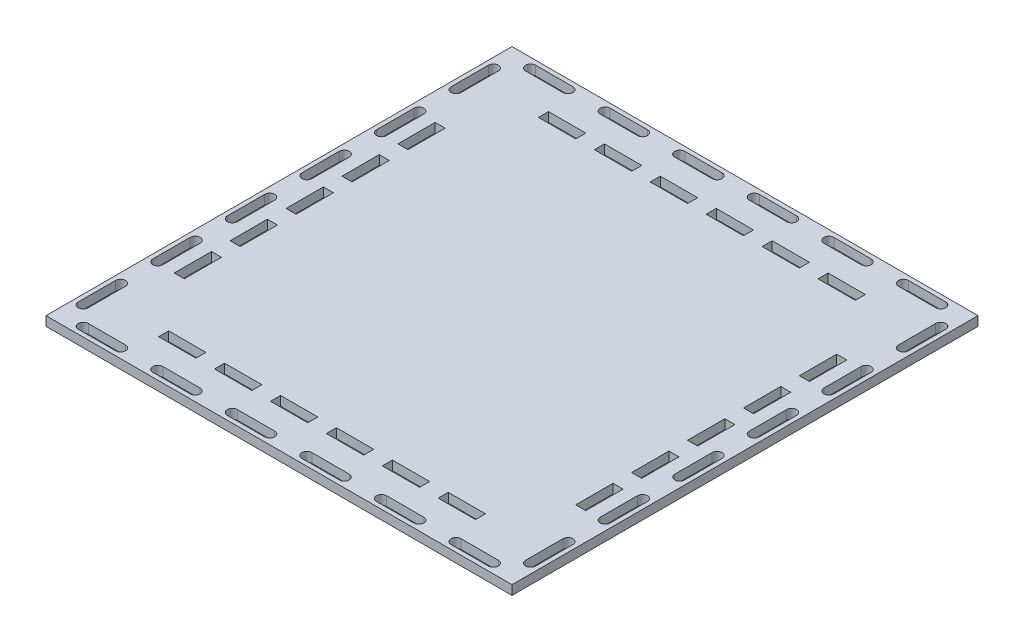
SolidWorks part; units mm, degrees
ref_plane "Front Plane" through (0, 0, 0) normal (0, 0, 1) x (1, 0, 0)
ref_plane "Top Plane" through (0, 0, 0) normal (0, 1, 0) x (1, 0, 0)
ref_plane "Right Plane" through (0, 0, 0) normal (1, 0, 0) x (0, 0, -1)
sketch "Sketch1" plane through (0, 0, 0) normal (0, 1, 0) x (1, 0, 0)
  line L1 (-158.75, -158.75) -> (158.75, -158.75)
  line L2 (-158.75, -158.75) -> (-158.75, 158.75)
  line L3 (-158.75, 158.75) -> (158.75, 158.75)
  line L4 (158.75, -158.75) -> (158.75, 158.75)
  line L5 (-158.75, -158.75) -> (158.75, 158.75) construction
  line L6 (-158.75, 158.75) -> (158.75, -158.75) construction
  point P0 (0, 0)
  dimension "D1" = 317.5
  dimension "D2" = 317.5
extrude "Boss-Extrude1" add sketch "Sketch1" along normal blind 6.35
sketch "Sketch2" plane through (0, 0, 0) normal (0, 1, 0) x (1, 0, 0)
  line L1 (-107.95, 132.8195) -> (-82.55, 132.8195)
  line L2 (-107.95, 132.8195) -> (-107.95, 125.9615)
  line L3 (-107.95, 125.9615) -> (-82.55, 125.9615)
  line L4 (-82.55, 132.8195) -> (-82.55, 125.9615)
  line L10 (-44.45, 132.8195) -> (-44.45, 125.9615)
  line L15 (-69.85, 125.9615) -> (-44.45, 125.9615)
  line L16 (-69.85, 132.8195) -> (-44.45, 132.8195)
  line L17 (-69.85, 132.8195) -> (-69.85, 125.9615)
  line L18 (-6.35, 132.8195) -> (-6.35, 125.9615)
  line L19 (-31.75, 125.9615) -> (-6.35, 125.9615)
  line L20 (-31.75, 132.8195) -> (-6.35, 132.8195)
  line L21 (-31.75, 132.8195) -> (-31.75, 125.9615)
  line L22 (31.75, 132.8195) -> (31.75, 125.9615)
  line L23 (6.35, 125.9615) -> (31.75, 125.9615)
  line L24 (6.35, 132.8195) -> (31.75, 132.8195)
  line L25 (6.35, 132.8195) -> (6.35, 125.9615)
  line L26 (69.85, 132.8195) -> (69.85, 125.9615)
  line L27 (44.45, 125.9615) -> (69.85, 125.9615)
  line L28 (44.45, 132.8195) -> (69.85, 132.8195)
  line L29 (44.45, 132.8195) -> (44.45, 125.9615)
  line L30 (107.95, 132.8195) -> (107.95, 125.9615)
  line L31 (82.55, 125.9615) -> (107.95, 125.9615)
  line L32 (82.55, 132.8195) -> (107.95, 132.8195)
  line L33 (82.55, 132.8195) -> (82.55, 125.9615)
  line L50 (184.15, 132.8195) -> (184.15, 125.9615) [skipped]
  line L51 (158.75, 125.9615) -> (184.15, 125.9615) [skipped]
  line L52 (158.75, 132.8195) -> (184.15, 132.8195) [skipped]
  line L53 (158.75, 132.8195) -> (158.75, 125.9615) [skipped]
  line L54 (222.25, 132.8195) -> (222.25, 125.9615) [skipped]
  line L55 (196.85, 125.9615) -> (222.25, 125.9615) [skipped]
  line L56 (196.85, 132.8195) -> (222.25, 132.8195) [skipped]
  line L57 (196.85, 132.8195) -> (196.85, 125.9615) [skipped]
  line L58 (260.35, 132.8195) -> (260.35, 125.9615) [skipped]
  line L59 (234.95, 125.9615) -> (260.35, 125.9615) [skipped]
  line L60 (234.95, 132.8195) -> (260.35, 132.8195) [skipped]
  line L61 (234.95, 132.8195) -> (234.95, 125.9615) [skipped]
  line L62 (-6.35, 125.9615) -> (6.35, 125.9615) construction
  line L63 (0, 125.9615) -> (0, 158.75) construction
  line L64 (146.05, 132.8195) -> (146.05, 125.9615) [skipped]
  line L65 (120.65, 125.9615) -> (146.05, 125.9615) [skipped]
  line L66 (120.65, 132.8195) -> (146.05, 132.8195) [skipped]
  line L67 (120.65, 132.8195) -> (120.65, 125.9615) [skipped]
  line L68 (158.75, 158.75) -> (-158.75, 158.75) construction
  line L75 (-140.208, 49.7615) -> (-140.208, 24.3615)
  line L76 (-140.208, 87.8615) -> (-133.35, 87.8615)
  line L77 (-140.208, 87.8615) -> (-140.208, 62.4615)
  line L78 (-140.208, 62.4615) -> (-133.35, 62.4615)
  line L79 (-133.35, 87.8615) -> (-133.35, 62.4615)
  line L80 (-140.208, 24.3615) -> (-133.35, 24.3615)
  line L81 (-133.35, 49.7615) -> (-133.35, 24.3615)
  line L82 (-140.208, 49.7615) -> (-133.35, 49.7615)
  line L83 (-140.208, 11.6615) -> (-140.208, -13.7385)
  line L84 (-140.208, -13.7385) -> (-133.35, -13.7385)
  line L85 (-133.35, 11.6615) -> (-133.35, -13.7385)
  line L86 (-140.208, 11.6615) -> (-133.35, 11.6615)
  line L87 (-140.208, -26.4385) -> (-140.208, -51.8385)
  line L88 (-140.208, -51.8385) -> (-133.35, -51.8385)
  line L89 (-133.35, -26.4385) -> (-133.35, -51.8385)
  line L90 (-140.208, -26.4385) -> (-133.35, -26.4385)
  line L91 (-140.208, -64.5385) -> (-140.208, -89.9385)
  line L92 (-140.208, -89.9385) -> (-133.35, -89.9385)
  line L93 (-133.35, -64.5385) -> (-133.35, -89.9385)
  line L94 (-140.208, -64.5385) -> (-133.35, -64.5385)
  line L95 (140.208, -64.5385) -> (133.35, -64.5385)
  line L96 (133.35, -64.5385) -> (133.35, -89.9385)
  line L97 (140.208, -89.9385) -> (133.35, -89.9385)
  line L98 (140.208, -64.5385) -> (140.208, -89.9385)
  line L99 (140.208, -26.4385) -> (133.35, -26.4385)
  line L100 (133.35, -26.4385) -> (133.35, -51.8385)
  line L101 (140.208, -51.8385) -> (133.35, -51.8385)
  line L102 (140.208, -26.4385) -> (140.208, -51.8385)
  line L103 (140.208, 11.6615) -> (133.35, 11.6615)
  line L104 (133.35, 11.6615) -> (133.35, -13.7385)
  line L105 (140.208, -13.7385) -> (133.35, -13.7385)
  line L106 (140.208, 11.6615) -> (140.208, -13.7385)
  line L107 (140.208, 49.7615) -> (133.35, 49.7615)
  line L108 (133.35, 49.7615) -> (133.35, 24.3615)
  line L109 (140.208, 24.3615) -> (133.35, 24.3615)
  line L110 (133.35, 87.8615) -> (133.35, 62.4615)
  line L111 (140.208, 62.4615) -> (133.35, 62.4615)
  line L112 (140.208, 87.8615) -> (140.208, 62.4615)
  line L113 (140.208, 87.8615) -> (133.35, 87.8615)
  line L114 (140.208, 49.7615) -> (140.208, 24.3615)
  line L115 (0, 0) -> (44.45, 0) construction
  line L116 (-139.7, 155.829) -> (-114.3, 155.829)
  line L117 (-6.35, -125.9615) -> (6.35, -125.9615) construction
  line L124 (82.55, -132.8195) -> (82.55, -125.9615)
  line L125 (82.55, -132.8195) -> (107.95, -132.8195)
  line L126 (82.55, -125.9615) -> (107.95, -125.9615)
  line L127 (107.95, -132.8195) -> (107.95, -125.9615)
  line L128 (44.45, -132.8195) -> (44.45, -125.9615)
  line L129 (44.45, -132.8195) -> (69.85, -132.8195)
  line L130 (44.45, -125.9615) -> (69.85, -125.9615)
  line L131 (69.85, -132.8195) -> (69.85, -125.9615)
  line L132 (6.35, -132.8195) -> (6.35, -125.9615)
  line L133 (6.35, -132.8195) -> (31.75, -132.8195)
  line L134 (6.35, -125.9615) -> (31.75, -125.9615)
  line L135 (31.75, -132.8195) -> (31.75, -125.9615)
  line L136 (-31.75, -132.8195) -> (-31.75, -125.9615)
  line L137 (-31.75, -132.8195) -> (-6.35, -132.8195)
  line L138 (-31.75, -125.9615) -> (-6.35, -125.9615)
  line L139 (-6.35, -132.8195) -> (-6.35, -125.9615)
  line L140 (-69.85, -132.8195) -> (-69.85, -125.9615)
  line L141 (-69.85, -132.8195) -> (-44.45, -132.8195)
  line L142 (-69.85, -125.9615) -> (-44.45, -125.9615)
  line L143 (-44.45, -132.8195) -> (-44.45, -125.9615)
  line L149 (-82.55, -132.8195) -> (-82.55, -125.9615)
  line L150 (-107.95, -125.9615) -> (-82.55, -125.9615)
  line L151 (-107.95, -132.8195) -> (-107.95, -125.9615)
  line L152 (-107.95, -132.8195) -> (-82.55, -132.8195)
  line L154 (-88.9, 155.829) -> (-63.5, 155.829)
  line L155 (-158.75, 158.75) -> (-158.75, -158.75) construction
  line L156 (-155.829, 139.7) -> (-155.829, 114.3)
  line L157 (-148.971, 114.3) -> (-148.971, 139.7)
  line L158 (-148.971, 63.5) -> (-148.971, 88.9)
  line L159 (-155.829, 88.9) -> (-155.829, 63.5)
  line L160 (-148.971, 12.7) -> (-148.971, 38.1)
  line L161 (-155.829, 38.1) -> (-155.829, 12.7)
  line L162 (-148.971, -38.1) -> (-148.971, -12.7)
  line L163 (-155.829, -12.7) -> (-155.829, -38.1)
  line L164 (-148.971, -88.9) -> (-148.971, -63.5)
  line L165 (-155.829, -63.5) -> (-155.829, -88.9)
  line L166 (-148.971, -139.7) -> (-148.971, -114.3)
  line L167 (-155.829, -114.3) -> (-155.829, -139.7)
  line L168 (-114.3, 148.971) -> (-139.7, 148.971)
  line L169 (-63.5, 148.971) -> (-88.9, 148.971)
  line L170 (-38.1, 155.829) -> (-12.7, 155.829)
  line L171 (-12.7, 148.971) -> (-38.1, 148.971)
  line L172 (12.7, 155.829) -> (38.1, 155.829)
  line L173 (38.1, 148.971) -> (12.7, 148.971)
  line L174 (63.5, 155.829) -> (88.9, 155.829)
  line L175 (88.9, 148.971) -> (63.5, 148.971)
  line L176 (114.3, 155.829) -> (139.7, 155.829)
  line L177 (139.7, 148.971) -> (114.3, 148.971)
  line L178 (139.7, -148.971) -> (114.3, -148.971)
  line L179 (114.3, -155.829) -> (139.7, -155.829)
  line L180 (88.9, -148.971) -> (63.5, -148.971)
  line L181 (63.5, -155.829) -> (88.9, -155.829)
  line L182 (38.1, -148.971) -> (12.7, -148.971)
  line L183 (12.7, -155.829) -> (38.1, -155.829)
  line L184 (-12.7, -148.971) -> (-38.1, -148.971)
  line L185 (-38.1, -155.829) -> (-12.7, -155.829)
  line L186 (-63.5, -148.971) -> (-88.9, -148.971)
  line L187 (-114.3, -148.971) -> (-139.7, -148.971)
  line L188 (-88.9, -155.829) -> (-63.5, -155.829)
  line L189 (-139.7, -155.829) -> (-114.3, -155.829)
  line L190 (155.829, -114.3) -> (155.829, -139.7)
  line L191 (148.971, -139.7) -> (148.971, -114.3)
  line L192 (155.829, -63.5) -> (155.829, -88.9)
  line L193 (148.971, -88.9) -> (148.971, -63.5)
  line L194 (155.829, -12.7) -> (155.829, -38.1)
  line L195 (148.971, -38.1) -> (148.971, -12.7)
  line L196 (155.829, 38.1) -> (155.829, 12.7)
  line L197 (148.971, 12.7) -> (148.971, 38.1)
  line L198 (155.829, 88.9) -> (155.829, 63.5)
  line L199 (148.971, 63.5) -> (148.971, 88.9)
  line L200 (148.971, 114.3) -> (148.971, 139.7)
  line L201 (155.829, 139.7) -> (155.829, 114.3)
  arc A0 (-148.971, 139.7) -> (-155.829, 139.7) centre (-152.4, 139.7) ccw
  arc A25 (-155.829, 114.3) -> (-148.971, 114.3) centre (-152.4, 114.3) ccw
  circle A48 centre (-152.4, 88.9) radius 3.429 [skipped]
  circle A49 centre (-152.4, 63.5) radius 3.429 [skipped]
  circle A50 centre (-152.4, 38.1) radius 3.429 [skipped]
  circle A51 centre (-152.4, 12.7) radius 3.429 [skipped]
  circle A52 centre (-152.4, -12.7) radius 3.429 [skipped]
  circle A53 centre (-152.4, -38.1) radius 3.429 [skipped]
  circle A54 centre (-152.4, -63.5) radius 3.429 [skipped]
  circle A55 centre (-152.4, -88.9) radius 3.429 [skipped]
  circle A56 centre (-152.4, -114.3) radius 3.429 [skipped]
  circle A57 centre (-152.4, -139.7) radius 3.429 [skipped]
  circle A58 centre (-152.4, -165.1) radius 3.429 [skipped]
  arc A59 (-148.971, 88.9) -> (-155.829, 88.9) centre (-152.4, 88.9) ccw
  arc A60 (-155.829, 63.5) -> (-148.971, 63.5) centre (-152.4, 63.5) ccw
  arc A61 (-148.971, 38.1) -> (-155.829, 38.1) centre (-152.4, 38.1) ccw
  arc A62 (-155.829, 12.7) -> (-148.971, 12.7) centre (-152.4, 12.7) ccw
  arc A63 (-148.971, -12.7) -> (-155.829, -12.7) centre (-152.4, -12.7) ccw
  arc A64 (-155.829, -38.1) -> (-148.971, -38.1) centre (-152.4, -38.1) ccw
  arc A65 (-148.971, -63.5) -> (-155.829, -63.5) centre (-152.4, -63.5) ccw
  arc A66 (-155.829, -88.9) -> (-148.971, -88.9) centre (-152.4, -88.9) ccw
  arc A67 (-148.971, -114.3) -> (-155.829, -114.3) centre (-152.4, -114.3) ccw
  arc A68 (-155.829, -139.7) -> (-148.971, -139.7) centre (-152.4, -139.7) ccw
  arc A69 (-139.7, 155.829) -> (-139.7, 148.971) centre (-139.7, 152.4) ccw
  arc A70 (-114.3, 148.971) -> (-114.3, 155.829) centre (-114.3, 152.4) ccw
  arc A71 (-63.5, 148.971) -> (-63.5, 155.829) centre (-63.5, 152.4) ccw
  arc A72 (-88.9, 155.829) -> (-88.9, 148.971) centre (-88.9, 152.4) ccw
  arc A73 (-12.7, 148.971) -> (-12.7, 155.829) centre (-12.7, 152.4) ccw
  arc A74 (-38.1, 155.829) -> (-38.1, 148.971) centre (-38.1, 152.4) ccw
  arc A75 (38.1, 148.971) -> (38.1, 155.829) centre (38.1, 152.4) ccw
  arc A76 (12.7, 155.829) -> (12.7, 148.971) centre (12.7, 152.4) ccw
  arc A77 (88.9, 148.971) -> (88.9, 155.829) centre (88.9, 152.4) ccw
  arc A78 (63.5, 155.829) -> (63.5, 148.971) centre (63.5, 152.4) ccw
  arc A79 (139.7, 148.971) -> (139.7, 155.829) centre (139.7, 152.4) ccw
  arc A80 (114.3, 155.829) -> (114.3, 148.971) centre (114.3, 152.4) ccw
  arc A81 (114.3, -155.829) -> (114.3, -148.971) centre (114.3, -152.4) cw
  arc A82 (139.7, -148.971) -> (139.7, -155.829) centre (139.7, -152.4) cw
  arc A83 (63.5, -155.829) -> (63.5, -148.971) centre (63.5, -152.4) cw
  arc A84 (88.9, -148.971) -> (88.9, -155.829) centre (88.9, -152.4) cw
  arc A85 (12.7, -155.829) -> (12.7, -148.971) centre (12.7, -152.4) cw
  arc A86 (38.1, -148.971) -> (38.1, -155.829) centre (38.1, -152.4) cw
  arc A87 (-38.1, -155.829) -> (-38.1, -148.971) centre (-38.1, -152.4) cw
  arc A88 (-12.7, -148.971) -> (-12.7, -155.829) centre (-12.7, -152.4) cw
  arc A89 (-88.9, -155.829) -> (-88.9, -148.971) centre (-88.9, -152.4) cw
  arc A90 (-63.5, -148.971) -> (-63.5, -155.829) centre (-63.5, -152.4) cw
  arc A91 (-114.3, -148.971) -> (-114.3, -155.829) centre (-114.3, -152.4) cw
  arc A92 (-139.7, -155.829) -> (-139.7, -148.971) centre (-139.7, -152.4) cw
  arc A93 (155.829, -139.7) -> (148.971, -139.7) centre (152.4, -139.7) cw
  arc A94 (148.971, -114.3) -> (155.829, -114.3) centre (152.4, -114.3) cw
  arc A95 (155.829, -88.9) -> (148.971, -88.9) centre (152.4, -88.9) cw
  arc A96 (148.971, -63.5) -> (155.829, -63.5) centre (152.4, -63.5) cw
  arc A97 (155.829, -38.1) -> (148.971, -38.1) centre (152.4, -38.1) cw
  arc A98 (148.971, -12.7) -> (155.829, -12.7) centre (152.4, -12.7) cw
  arc A99 (155.829, 12.7) -> (148.971, 12.7) centre (152.4, 12.7) cw
  arc A100 (148.971, 38.1) -> (155.829, 38.1) centre (152.4, 38.1) cw
  arc A101 (155.829, 63.5) -> (148.971, 63.5) centre (152.4, 63.5) cw
  arc A102 (148.971, 88.9) -> (155.829, 88.9) centre (152.4, 88.9) cw
  arc A103 (155.829, 114.3) -> (148.971, 114.3) centre (152.4, 114.3) cw
  arc A104 (148.971, 139.7) -> (155.829, 139.7) centre (152.4, 139.7) cw
  point P11 (0, 125.9615)
  dimension "D1" = 6.858
  dimension "D5" = 6.858
  dimension "D2" = 25.4
  dimension "D3" = 19.05
  dimension "D4" = 6.35
  dimension "D6" = 6.35
  dimension "D7" = 25.4
  dimension "D10" = 13
  dimension "D12" = 19.05
  dimension "D9" = 10
  dimension "D8" = 5
  dimension "D11" = 6
extrude "Cut-Extrude2" cut sketch "Sketch2" along normal through all
